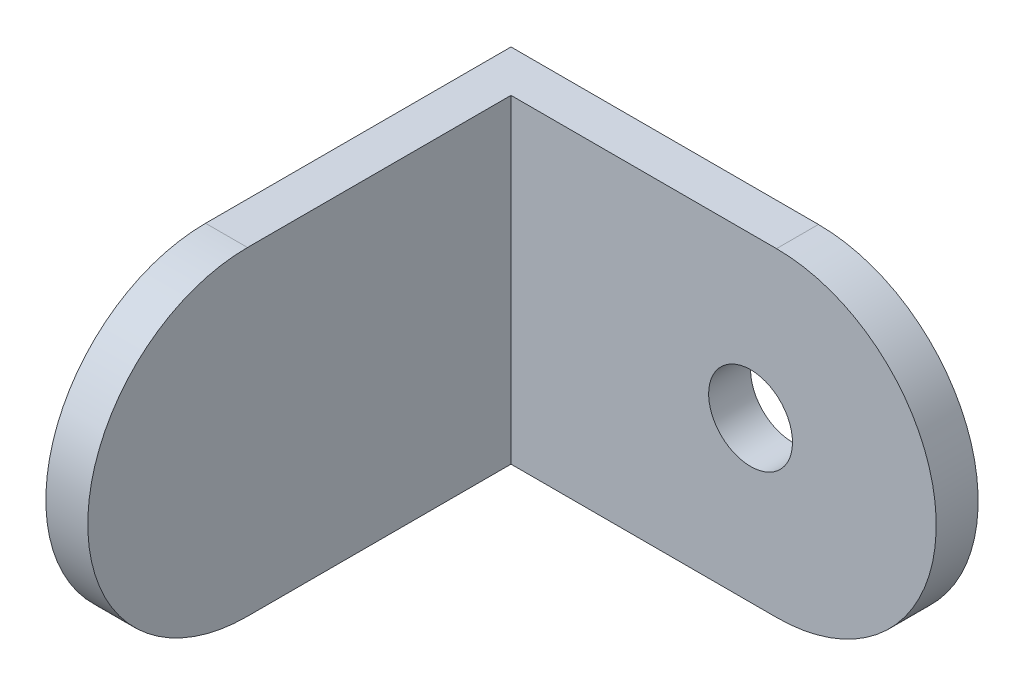
SolidWorks part; units mm, degrees
ref_plane "Front Plane" through (0, 0, 0) normal (0, 0, 1) x (1, 0, 0)
ref_plane "Top Plane" through (0, 0, 0) normal (0, 1, 0) x (1, 0, 0)
ref_plane "Right Plane" through (0, 0, 0) normal (1, 0, 0) x (0, 0, -1)
ref_plane "Plane1" through (0, 0, 15.3) normal (0, 0, -1) x (-1, 0, 0)
sketch "Sketch1" plane through (0, 0, 15.3) normal (0, 0, -1) x (-1, 0, 0)
  line L0 (-2.1, 8) -> (0, 8)
  line L1 (0, 8) -> (0, 16)
  line L2 (0, 16) -> (-2.1, 16)
  line L3 (-2.1, 16) -> (-2.1, 8)
  line L4 (-2.1, 8) -> (0, 8) construction
revolve "Revolve1" add sketch "Sketch1" angle 180 about L4
sketch "Sketch2" plane through (0, 0, 15.3) normal (0, 0, -1) x (-1, 0, 0)
  line L0 (-2.1, 0) -> (-2.1, 16)
  line L1 (-2.1, 16) -> (0, 16)
  line L2 (0, 16) -> (0, 0)
  line L3 (0, 0) -> (-2.1, 0)
extrude "Boss-Extrude1" add sketch "Sketch2" along normal blind 13.2
sketch "Sketch3" plane through (0, 0, 2.1) normal (0, 0, -1) x (-1, 0, 0)
  line L0 (-15.4, 16) -> (0, 16)
  line L1 (0, 16) -> (0, 0)
  line L2 (0, 0) -> (-15.4, 0)
  arc A0 (-15.4, 0) -> (-15.4, 16) centre (-15.4, 8) cw
extrude "Boss-Extrude2" add sketch "Sketch3" along normal blind 2.1
hole_wizard "Ø4.2 (4.2) Diameter Hole1" positions "Sketch5" profile "Sketch4" hole size "Ø4.2" standard "ANSI Metric"
sketch "Sketch5" plane through (0, 0, 0) normal (0, 0, -1) x (-1, 0, 0)
  point P0 (-14.1, 8)
sketch "Sketch4" plane through (14.1, 8, 0) normal (1, 0, 0) x (0, 1, 0)
  line L0 (0, 0) -> (0, 23.3)
  line L1 (0, 23.3) -> (2.1, 23.3)
  line L2 (2.1, 23.3) -> (2.1, 0)
  line L5 (2.1, 0) -> (0, 0)
  line L11 (0, -6.35) -> (0, 107.95) construction
  dimension "Thru Hole Dia." = 4.2
  dimension "Thru Hole Depth" = 23.3
